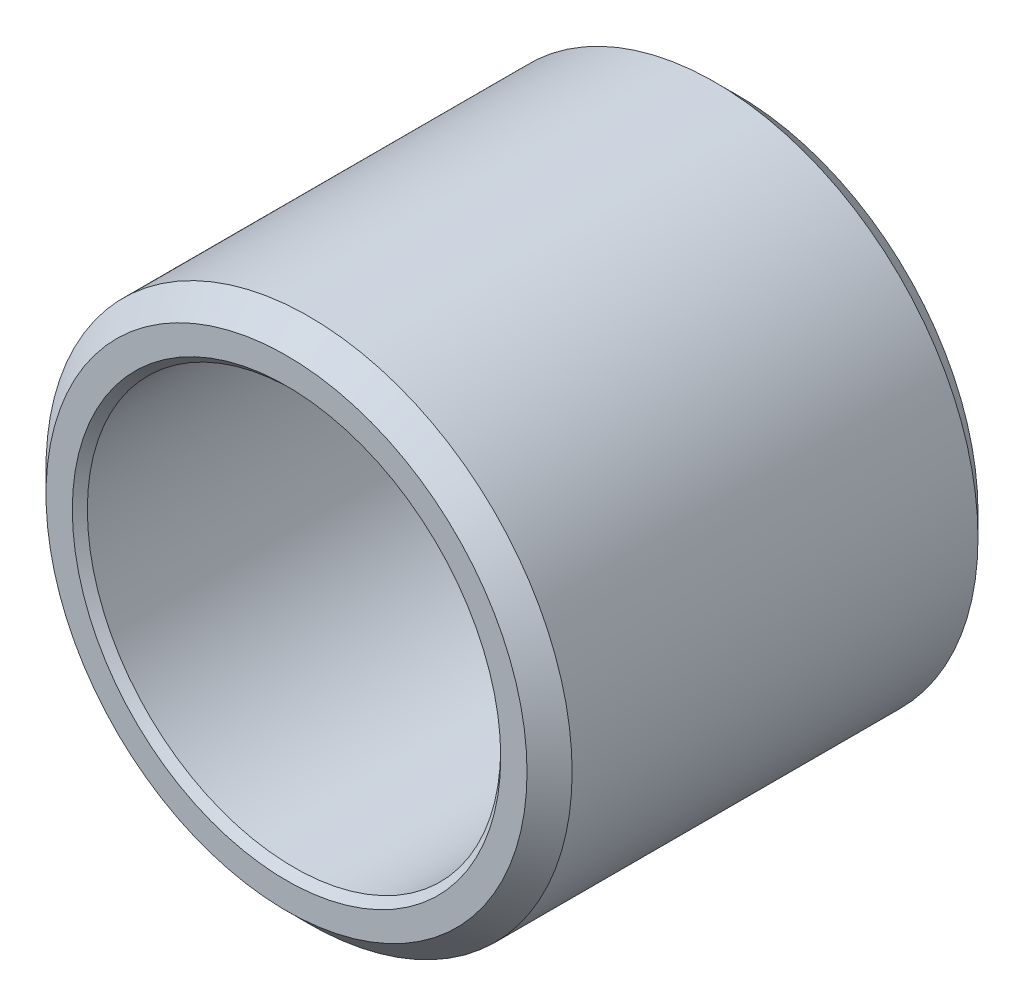
SolidWorks part; units mm, degrees
material "20"
ref_plane "前视基准面" through (0, 0, 0) normal (0, 0, 1) x (1, 0, 0)
ref_plane "上视基准面" through (0, 0, 0) normal (0, 1, 0) x (1, 0, 0)
ref_plane "右视基准面" through (0, 0, 0) normal (1, 0, 0) x (0, 0, -1)
sketch "草图1" plane through (0, 0, 0) normal (0, 0, 1) x (1, 0, 0)
  circle A0 centre (0, 0) radius 27.5
  circle A1 centre (0, 0) radius 35
  dimension "D1" = 70
  dimension "D2" = 55
extrude "凸台-拉伸1" add sketch "草图1" along normal blind 60
chamfer "倒角1" distance 3 angle 45 2 edges at (35, 0, 0) (35, 0, 60)
sketch "草图2" plane through (0, 0, 0) normal (0, 1, 0) x (1, 0, 0)
  line L0 (0, 0) -> (0, -70.5405) construction
  line L1 (32, 0) -> (-32, 0) construction
  line L2 (0, -4.5) -> (29, -4.5)
  line L3 (0, -4.5) -> (0, -6.7)
  line L4 (0, -6.7) -> (29, -6.7)
  line L5 (29, -4.5) -> (29, -6.7)
  dimension "D1" = 29
  dimension "D2" = 4.5
  dimension "D3" = 2.2
revolve "切除-旋转1" cut sketch "草图2" angle 360 about L0
chamfer "倒角2" distance 1 angle 45 2 edges at (27.5, 0, 0) (27.5, 0, 60)
